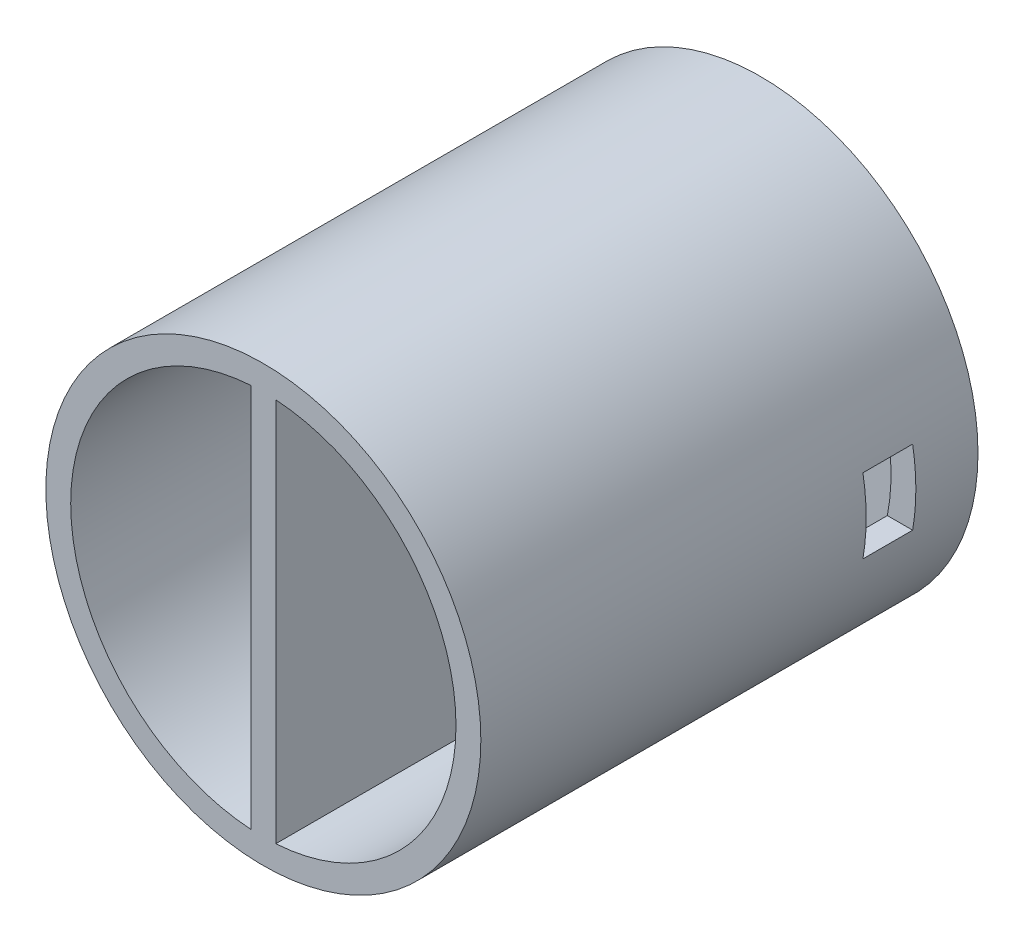
SolidWorks part; units mm, degrees
ref_plane "Front Plane" through (0, 0, 0) normal (0, 0, 1) x (1, 0, 0)
ref_plane "Top Plane" through (0, 0, 0) normal (0, 1, 0) x (1, 0, 0)
ref_plane "Right Plane" through (0, 0, 0) normal (1, 0, 0) x (0, 0, -1)
sketch "Sketch1" plane through (0, 0, 0) normal (0, 0, 1) x (1, 0, 0)
  circle A0 centre (0, 0) radius 17.5
  dimension "D1" = 35
extrude "Boss-Extrude1" add sketch "Sketch1" along normal blind 2
sketch "Sketch2" plane through (0, 0, 2) normal (0, 0, 1) x (1, 0, 0)
  line L2 (-1, 15.4677) -> (-1, -15.4677)
  line L4 (1, 15.4677) -> (1, -15.4677)
  line L5 (-0.9625, 15.4701) -> (0.9625, -15.4701) construction
  line L6 (-0.9625, -15.4701) -> (0.9625, 15.4701) construction
  circle A0 centre (0, 0) radius 17.5
  arc A1 (-1, 15.4677) -> (-1, -15.4677) centre (0, 0) ccw
  arc A2 (1, -15.4677) -> (1, 15.4677) centre (0, 0) ccw
  dimension "D1" = 31
  dimension "D2" = 35
  dimension "D3" = 2
extrude "Boss-Extrude2" add sketch "Sketch2" along normal blind 38
sketch "Sketch3" plane through (0, 0, 2) normal (0, 0, 1) x (1, 0, 0)
  line L0 (-19.6396, 0) -> (22.0956, 0) construction
  line L1 (5, 3) -> (9, 3)
  line L2 (5, 3) -> (5, -3)
  line L3 (5, -3) -> (9, -3)
  line L4 (9, 3) -> (9, -3)
  line L5 (5, 3) -> (9, -3) construction
  line L6 (5, -3) -> (9, 3) construction
  line L7 (0, 20.3964) -> (0, -23.4964) construction
  line L8 (-5, -3) -> (-9, -3)
  line L9 (-9, 3) -> (-9, -3)
  line L10 (-5, 3) -> (-9, 3)
  line L11 (-5, 3) -> (-5, -3)
  point P0 (7, 0)
  point P6 (0, 0)
  point P11 (0, 0)
  dimension "D1" = 4
  dimension "D2" = 6
  dimension "D3" = 5
extrude "Cut-Extrude1" cut sketch "Sketch3" against normal through all
sketch "Sketch4" plane through (-1, 0, 0) normal (-1, 0, 0) x (0, 0, 1)
  line L0 (-4.6099, 0) -> (44.6588, 0) construction
  line L1 (5, 3) -> (9, 3)
  line L2 (5, 3) -> (5, -3)
  line L3 (5, -3) -> (9, -3)
  line L4 (9, 3) -> (9, -3)
  line L5 (5, 3) -> (9, -3) construction
  line L6 (5, -3) -> (9, 3) construction
  line L7 (0, 17.5) -> (0, -17.5) construction
  point P0 (7, 0)
  point P8 (0, 0)
  dimension "D1" = 4
  dimension "D2" = 6
  dimension "D3" = 5
extrude "Cut-Extrude2" cut sketch "Sketch4" along normal through all
mirror "Mirror1" about plane through (0, 0, 0) normal (1, 0, 0) of "Cut-Extrude2"
